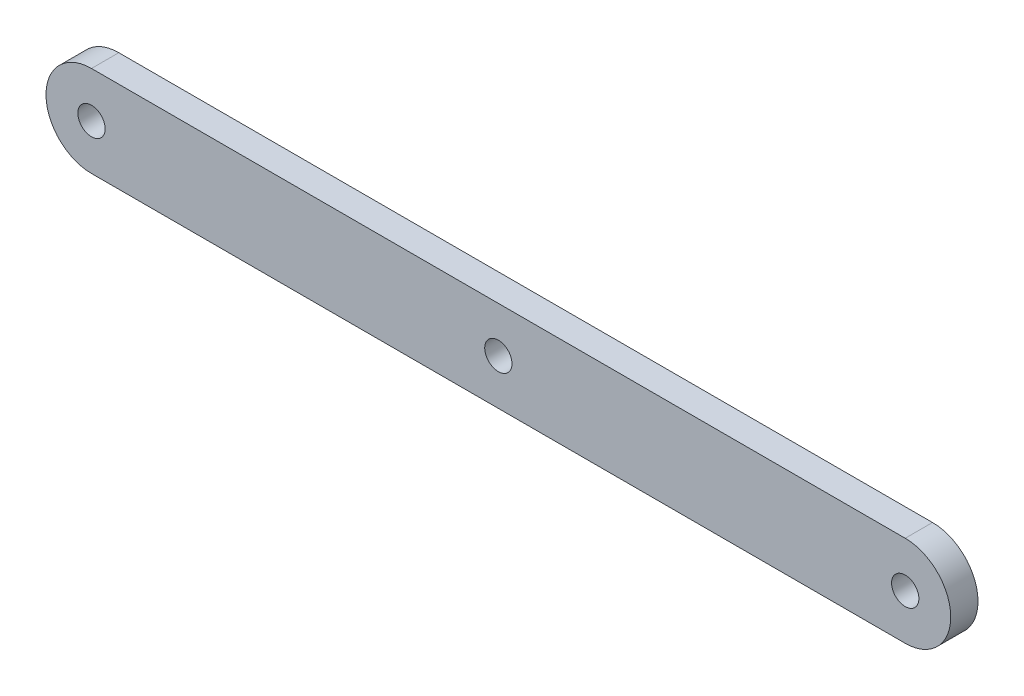
SolidWorks part; units mm, degrees
ref_plane "前基準面" through (0, 0, 0) normal (0, 0, 1) x (1, 0, 0)
ref_plane "上基準面" through (0, 0, 0) normal (0, 1, 0) x (1, 0, 0)
ref_plane "右基準面" through (0, 0, 0) normal (1, 0, 0) x (0, 0, -1)
sketch "草圖1" plane through (0, 0, 0) normal (0, 0, 1) x (1, 0, 0)
  line L0 (-22.36, 0) -> (22.36, 0) construction
  line L1 (-22.36, 2.5) -> (22.36, 2.5)
  line L2 (-22.36, -2.5) -> (22.36, -2.5)
  arc A0 (-22.36, 2.5) -> (-22.36, -2.5) centre (-22.36, 0) ccw
  arc A1 (22.36, -2.5) -> (22.36, 2.5) centre (22.36, 0) ccw
  circle A2 centre (22.36, 0) radius 0.75
  circle A3 centre (-22.36, 0) radius 0.75
  circle A4 centre (0, 0) radius 0.75
  point P2 (0, 0)
  dimension "D2" = 2.5
  dimension "D3" = 1.5
  dimension "D1" = 44.72
extrude "填料-伸長1" add sketch "草圖1" along normal mid plane 1.5
